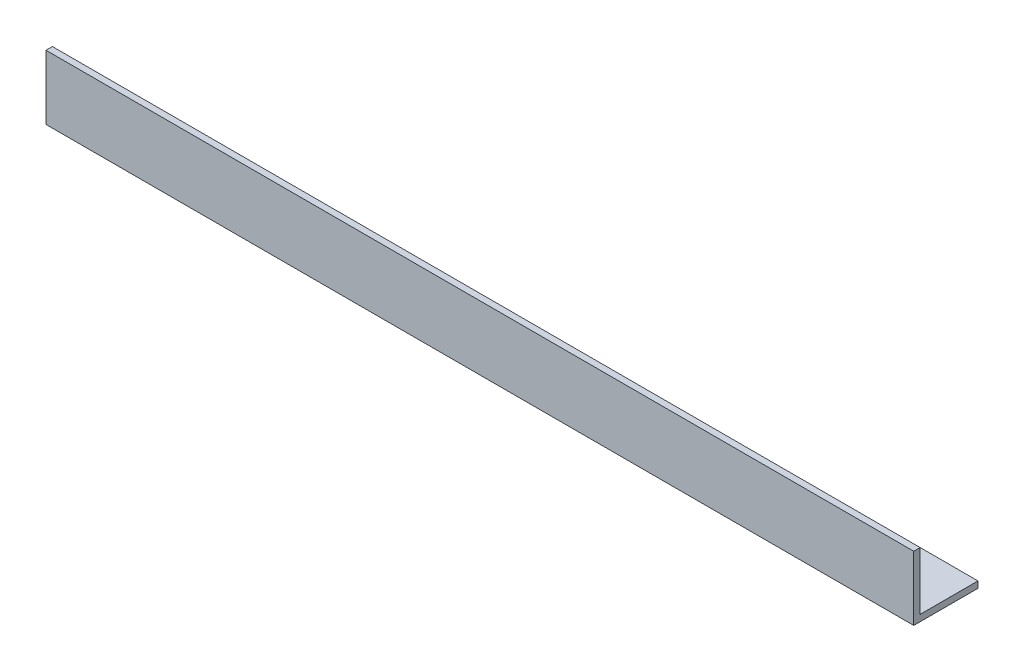
SolidWorks part; units mm, degrees
ref_plane "Front Plane" through (0, 0, 0) normal (0, 0, 1) x (1, 0, 0)
ref_plane "Top Plane" through (0, 0, 0) normal (0, 1, 0) x (1, 0, 0)
ref_plane "Right Plane" through (0, 0, 0) normal (1, 0, 0) x (0, 0, -1)
sketch "Sketch1" plane through (0, 0, 0) normal (1, 0, 0) x (0, 0, -1)
  line L0 (0, 20) -> (0, 0)
  line L1 (0, 0) -> (20, 0)
  line L2 (20, 0) -> (20, 2)
  line L3 (20, 2) -> (2, 2)
  line L4 (2, 2) -> (2, 20)
  line L5 (0, 20) -> (2, 20)
  dimension "D1" = 20
  dimension "D2" = 20
  dimension "D3" = 2
  dimension "D4" = 2
extrude "Boss-Extrude1" add sketch "Sketch1" along normal blind 270
